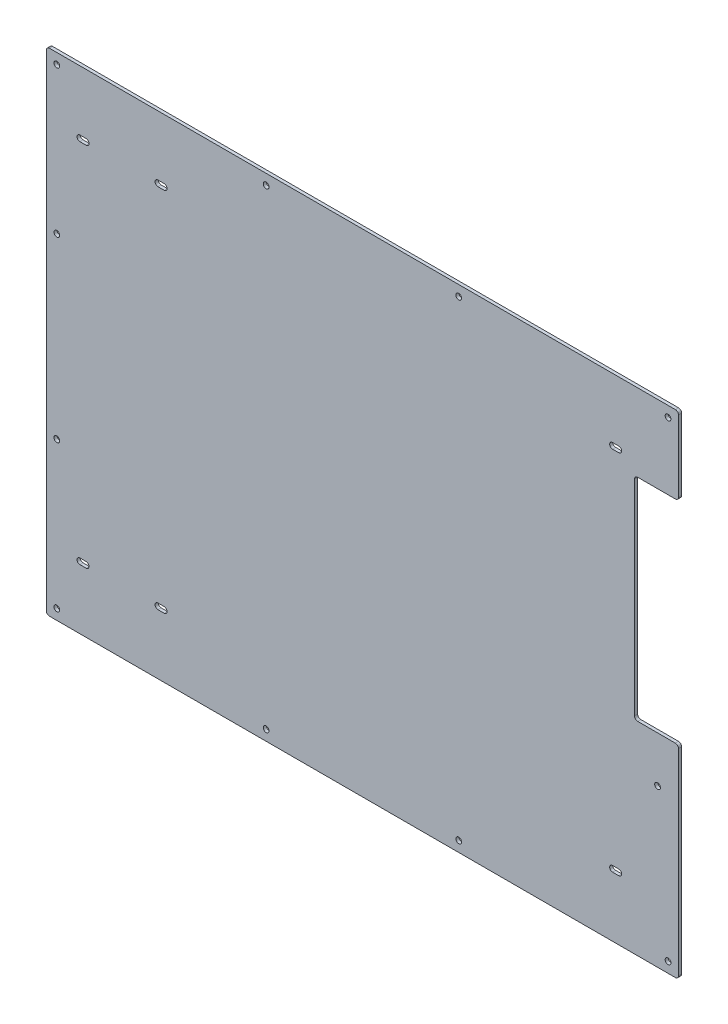
SolidWorks part; units mm, degrees
material "Acrylic (Medium-high impact)"
ref_plane "Front" through (0, 0, 0) normal (0, 0, 1) x (1, 0, 0)
ref_plane "Top" through (0, 0, 0) normal (0, 1, 0) x (1, 0, 0)
ref_plane "Right" through (0, 0, 0) normal (1, 0, 0) x (0, 0, -1)
sketch "Sketch1" plane through (0, 0, 0) normal (0, 0, 1) x (1, 0, 0)
  line L0 (0, 450) -> (604, 450) construction
  line L1 (0, 0) -> (604, 0)
  line L2 (0, 0) -> (0, 470)
  line L3 (0, 470) -> (604, 470)
  line L4 (604, 0) -> (604, 470)
  dimension "D1" = 604
  dimension "D2" = 470
  dimension "D3" = 20
extrude "Boss-Extrude1" add sketch "Sketch1" along normal blind 3
fillet "Fillet1" radius 3 4 edges at (0, 0, 1.5) (604, 0, 1.5) (0, 470, 1.5) (604, 470, 1.5)
hole_wizard "M5 Clearance Hole1" positions "Sketch4" profile "Sketch3" hole size "M5" standard "ANSI Metric" end condition through all
sketch "Sketch4" plane through (0, 0, 0) normal (0, 0, -1) x (-1, 0, 0)
  line L0 (-210, 460) -> (-10, 460) construction
  line L1 (-10, 460) -> (0, 460) construction
  line L2 (0, 467) -> (0, 3) construction
  line L5 (-210, 460) -> (-246, 460) construction
  line L8 (-302, 470) -> (-302, 460) construction
  line L9 (-601, 470) -> (-3, 470) construction
  line L10 (-358, 460) -> (-246, 460) construction
  line L14 (-394, 460) -> (-358, 460) construction
  line L15 (-594, 460) -> (-604, 460) construction
  line L16 (-394, 460) -> (-594, 460) construction
  line L17 (-10, 10) -> (0, 10) construction
  line L20 (-10, 10) -> (-210, 10) construction
  line L21 (-210, 10) -> (-246, 10) construction
  line L22 (-246, 10) -> (-358, 10) construction
  line L27 (-210, 460) -> (-210, 10) construction
  line L30 (-10, 10) -> (-10, 460) construction
  line L32 (-394, 10) -> (-358, 10) construction
  line L33 (-594, 10) -> (-394, 10) construction
  line L34 (-594, 10) -> (-604, 10) construction
  line L35 (-3, 0) -> (-601, 0) construction
  line L36 (-544, 470) -> (-544, 410) construction
  line L37 (-601, 470) -> (-3, 470) construction
  line L38 (-544, 410) -> (-544, 60) construction
  line L39 (-544, 60) -> (-544, 0) construction
  line L40 (-3, 0) -> (-601, 0) construction
  line L43 (-604, 3) -> (-604, 467) construction
  line L44 (-35, 470) -> (-35, 410) construction
  line L45 (-35, 410) -> (-35, 60) construction
  line L46 (-35, 60) -> (-35, 0) construction
  line L49 (0, 467) -> (0, 3) construction
  line L50 (-109.625, 470) -> (-109.625, 410) construction
  line L51 (-109.625, 410) -> (-109.625, 60) construction
  line L52 (-109.625, 60) -> (-109.625, 0) construction
  point P0 (-594, 460)
  point P2 (-394, 460)
  point P4 (-210, 460)
  point P6 (-10, 460)
  point P8 (-10, 10)
  point P10 (-210, 10)
  point P12 (-394, 10)
  point P14 (-594, 10)
  point P98 (-544, 410)
  point P102 (-544, 60)
  point P120 (-35, 410)
  point P122 (-35, 60)
  point P138 (-109.625, 410)
  point P140 (-109.625, 60)
  dimension "D1" = 10
  dimension "D2" = 200
  dimension "D4" = 10
  dimension "D5" = 10
  dimension "D6" = 60
  dimension "D7" = 60
  dimension "D8" = 35
  dimension "D9" = 109.625
sketch "Sketch3" plane through (594, 460, 0) normal (1, 0, 0) x (0, 1, 0)
  line L0 (0, 0) -> (0, 3)
  line L1 (0, 3) -> (2.75, 3)
  line L2 (2.75, 3) -> (2.75, 0)
  line L5 (2.75, 0) -> (0, 0)
  line L11 (0, -6.35) -> (0, 107.95) construction
  dimension "Thru Hole Dia." = 5.5
  dimension "Thru Hole Depth" = 3
hole_wizard "M5 Manufacturing Fixturing Hole" positions "Sketch12" profile "Sketch13" hole size "M5" standard "ANSI Metric" end condition through all
sketch "Sketch12" plane through (0, 0, 3) normal (0, 0, 1) x (1, 0, 0)
  line L0 (0, 467) -> (0, 3) construction
  line L1 (10, 320) -> (10, 150) construction
  line L4 (10, 150) -> (10, 0) construction
  line L5 (3, 0) -> (601, 0) construction
  line L8 (10, 320) -> (10, 470) construction
  line L9 (601, 470) -> (3, 470) construction
  line L11 (584, 470) -> (584, 320) construction
  line L12 (584, 320) -> (584, 150) construction
  line L13 (584, 150) -> (584, 0) construction
  line L16 (604, 3) -> (604, 467) construction
  point P0 (10, 320)
  point P2 (10, 150)
  point P28 (584, 320)
  point P30 (584, 150)
  dimension "D1" = 10
  dimension "D2" = 150
  dimension "D3" = 320
  dimension "D4" = 20
sketch "Sketch13" plane through (10, 320, 3) normal (1, 0, 0) x (0, -1, 0)
  line L0 (0, 0) -> (0, 3)
  line L1 (0, 3) -> (2.75, 3)
  line L2 (2.75, 3) -> (2.75, 0)
  line L5 (2.75, 0) -> (0, 0)
  line L11 (0, -6.35) -> (0, 107.95) construction
  dimension "Thru Hole Dia." = 5.5
  dimension "Thru Hole Depth" = 3
sketch "Sketch5" [suppressed] plane through (0, 0, 3) normal (0, 0, 1) x (1, 0, 0)
  line L0 (3, 0) -> (601, 0) construction
  line L1 (566.25, 20) -> (594.25, 20)
  line L2 (566.25, 20) -> (566.25, 67)
  line L3 (566.25, 67) -> (594.25, 67)
  line L4 (594.25, 20) -> (594.25, 67)
  line L5 (604, 3) -> (604, 467) construction
  line L6 (566.25, 43.5) -> (560.25, 43.5) construction
  line L7 (580.25, 67) -> (580.25, 20) construction
  line L9 (545.25, 14.25) -> (573.25, 14.25) construction
  circle A0 centre (560.25, 43.5) radius 1.6
  circle A1 centre (600.25, 43.5) radius 1.6
  circle A2 centre (394, 10) radius 4.75 construction
  circle A4 centre (594, 10) radius 4.75 construction
  dimension "D5" = 3.2
  dimension "D6" = 40
  dimension "D3" = 3.75
  dimension "D7" = 9.5
  dimension "D1" = 20
  dimension "D2" = 47
  dimension "D4" = 28
  dimension "D8" = 5.75
extrude "PSU Cutout" [suppressed] cut sketch "Sketch5" against normal through all
fillet "Fillet2" [suppressed] radius 0.5
sketch "Sketch9" plane through (0, 0, 3) normal (0, 0, 1) x (1, 0, 0)
  line L0 (32, 410) -> (38, 410) construction
  line L1 (32, 412.75) -> (38, 412.75)
  line L2 (32, 407.25) -> (38, 407.25)
  line L3 (106.625, 410) -> (112.625, 410) construction
  line L4 (106.625, 412.75) -> (112.625, 412.75)
  line L5 (106.625, 407.25) -> (112.625, 407.25)
  line L6 (32, 60) -> (38, 60) construction
  line L7 (32, 62.75) -> (38, 62.75)
  line L8 (32, 57.25) -> (38, 57.25)
  line L9 (106.625, 60) -> (112.625, 60) construction
  line L10 (106.625, 62.75) -> (112.625, 62.75)
  line L11 (106.625, 57.25) -> (112.625, 57.25)
  line L12 (541, 410) -> (547, 410) construction
  line L13 (541, 412.75) -> (547, 412.75)
  line L14 (541, 407.25) -> (547, 407.25)
  line L15 (541, 60) -> (547, 60) construction
  line L16 (541, 62.75) -> (547, 62.75)
  line L17 (541, 57.25) -> (547, 57.25)
  arc A0 (32, 412.75) -> (32, 407.25) centre (32, 410) ccw
  arc A1 (38, 407.25) -> (38, 412.75) centre (38, 410) ccw
  circle A2 centre (35, 410) radius 2.75 construction
  arc A3 (106.625, 412.75) -> (106.625, 407.25) centre (106.625, 410) ccw
  arc A4 (112.625, 407.25) -> (112.625, 412.75) centre (112.625, 410) ccw
  circle A5 centre (109.625, 410) radius 2.75 construction
  arc A6 (32, 62.75) -> (32, 57.25) centre (32, 60) ccw
  arc A7 (38, 57.25) -> (38, 62.75) centre (38, 60) ccw
  arc A8 (106.625, 62.75) -> (106.625, 57.25) centre (106.625, 60) ccw
  arc A9 (112.625, 57.25) -> (112.625, 62.75) centre (112.625, 60) ccw
  arc A10 (541, 412.75) -> (541, 407.25) centre (541, 410) ccw
  arc A11 (547, 407.25) -> (547, 412.75) centre (547, 410) ccw
  arc A12 (541, 62.75) -> (541, 57.25) centre (541, 60) ccw
  arc A13 (547, 57.25) -> (547, 62.75) centre (547, 60) ccw
  circle A14 centre (544, 410) radius 2.75 construction
  circle A15 centre (544, 410) radius 2.75 construction
  circle A16 centre (544, 60) radius 2.75 construction
  circle A17 centre (544, 60) radius 2.75 construction
  circle A18 centre (35, 60) radius 2.75 construction
  circle A19 centre (35, 60) radius 2.75 construction
  circle A20 centre (109.625, 60) radius 2.75 construction
  circle A21 centre (109.625, 60) radius 2.75 construction
  circle A22 centre (35, 410) radius 2.75 construction
  circle A23 centre (109.625, 410) radius 2.75 construction
  point P2 (35, 410)
  point P12 (109.625, 410)
  point P22 (35, 60)
  point P29 (109.625, 60)
  point P37 (544, 410)
  point P45 (544, 60)
  dimension "D1" = 6
extrude "Cut-Extrude5" cut sketch "Sketch9" against normal through all
sketch "Sketch6" plane through (0, 0, 3) normal (0, 0, 1) x (1, 0, 0)
  line L0 (604, 3) -> (604, 467) construction
  line L1 (604, 396) -> (562, 396)
  line L2 (604, 396) -> (604, 194)
  line L3 (604, 194) -> (562, 194)
  line L4 (562, 396) -> (562, 194)
  line L5 (601, 470) -> (3, 470) construction
  dimension "D1" = 42
  dimension "D2" = 202
  dimension "D3" = 276
extrude "Cut-Extrude2" cut sketch "Sketch6" against normal through all
fillet "Fillet3" radius 3 4 edges at (562, 194, 1.5) (562, 396, 1.5) (604, 194, 1.5) (604, 396, 1.5)
sketch "Sketch7" [suppressed] plane through (0, 0, 3) normal (0, 0, 1) x (1, 0, 0)
  line L0 (523, 0) -> (523, 70) construction
  line L1 (3, 0) -> (601, 0) construction
  line L2 (523, 70) -> (604, 70) construction
  line L3 (604, 3) -> (604, 467) construction
  line L4 (513, 0) -> (513, 80)
  line L5 (513, 80) -> (604, 80)
  line L6 (604, 80) -> (604, 470)
  line L7 (604, 470) -> (0, 470)
  line L8 (0, 470) -> (0, 0)
  line L9 (0, 0) -> (513, 0)
  line L10 (601, 470) -> (3, 470) construction
  circle A0 centre (523, 60) radius 2.75 construction
  dimension "D1" = 10
  dimension "D2" = 10
  dimension "D3" = 10
extrude "Cut-Extrude3" [suppressed] cut sketch "Sketch7" against normal through all
fillet "Fillet4" [suppressed] radius 3
sketch "Sketch8" [suppressed] plane through (0, 0, 3) normal (0, 0, 1) x (1, 0, 0)
  line L0 (523, 60) -> (523, 10) construction
  line L1 (523, 10) -> (599, 10) construction
  circle A0 centre (523, 10) radius 2.65
  dimension "D1" = 5.3
extrude "Cut-Extrude4" [suppressed] cut sketch "Sketch8" against normal through all
sketch "Sketch10" [suppressed] plane through (0, 0, 3) normal (0, 0, 1) x (1, 0, 0)
  line L1 (604, 20) -> (554, 20)
  line L2 (604, 20) -> (604, 100)
  line L3 (604, 100) -> (554, 100)
  line L4 (554, 20) -> (554, 100)
  line L5 (604, 3) -> (604, 467) construction
  line L6 (3, 0) -> (601, 0) construction
  dimension "D1" = 80
  dimension "D2" = 50
  dimension "D3" = 20
extrude "Cut-Extrude6" [suppressed] cut sketch "Sketch10" against normal through all
fillet "Fillet5" [suppressed] radius 3
other "120V Side Move Face" [suppressed] parameters "D1"=0.0762
other "Ethernet Side Move Face" [suppressed] parameters "D1"=0.0762
sketch "Sketch11" [suppressed] plane through (0, 0, 3) normal (0, 0, 1) x (1, 0, 0)
  line L0 (554, 20) -> (555.1225, 21.1225) construction
  line L1 (554, 20) -> (601, 20) construction
  line L2 (554, 100) -> (555.1225, 98.8775) construction
  line L3 (601, 100) -> (554, 100) construction
  circle A0 centre (555.1225, 21.1225) radius 1.5875
  circle A1 centre (555.1225, 98.8775) radius 1.5875
  dimension "D3" = 45
  dimension "D1" = 45
  dimension "D2" = 1.5875
  dimension "D4" = 1.5875
extrude "Cut-Extrude7" [suppressed] cut sketch "Sketch11" against normal through all
fillet "Fillet6" [suppressed] radius 1
